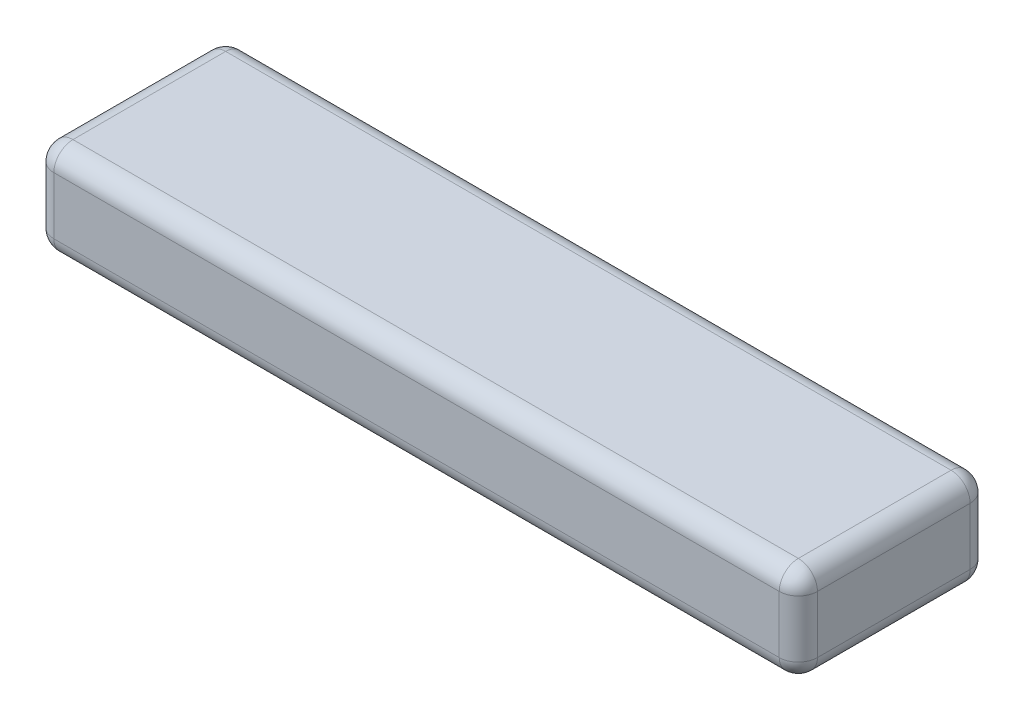
SolidWorks part; units mm, degrees
ref_plane "Front Plane" through (0, 0, 0) normal (0, 0, 1) x (1, 0, 0)
ref_plane "Top Plane" through (0, 0, 0) normal (0, 1, 0) x (1, 0, 0)
ref_plane "Right Plane" through (0, 0, 0) normal (1, 0, 0) x (0, 0, -1)
sketch "Sketch1" plane through (0, 0, 0) normal (0, 1, 0) x (1, 0, 0)
  line L1 (-20, 5) -> (20, 5)
  line L2 (-20, 5) -> (-20, -5)
  line L3 (-20, -5) -> (20, -5)
  line L4 (20, 5) -> (20, -5)
  line L5 (-20, 5) -> (20, -5) construction
  line L6 (-20, -5) -> (20, 5) construction
  point P0 (0, 0)
  dimension "D1" = 40
  dimension "D2" = 10
extrude "Boss-Extrude1" add sketch "Sketch1" along normal blind 5
fillet "Fillet1" radius 1 12 edges at (-20, 2.5, -5) (0, 0, -5) (-20, 0, 0) (20, 2.5, -5) (20, 0, 0) (-20, 2.5, 5) (20, 2.5, 5) (0, 0, 5) (0, 5, 5) (-20, 5, 0) (0, 5, -5) (20, 5, 0)
